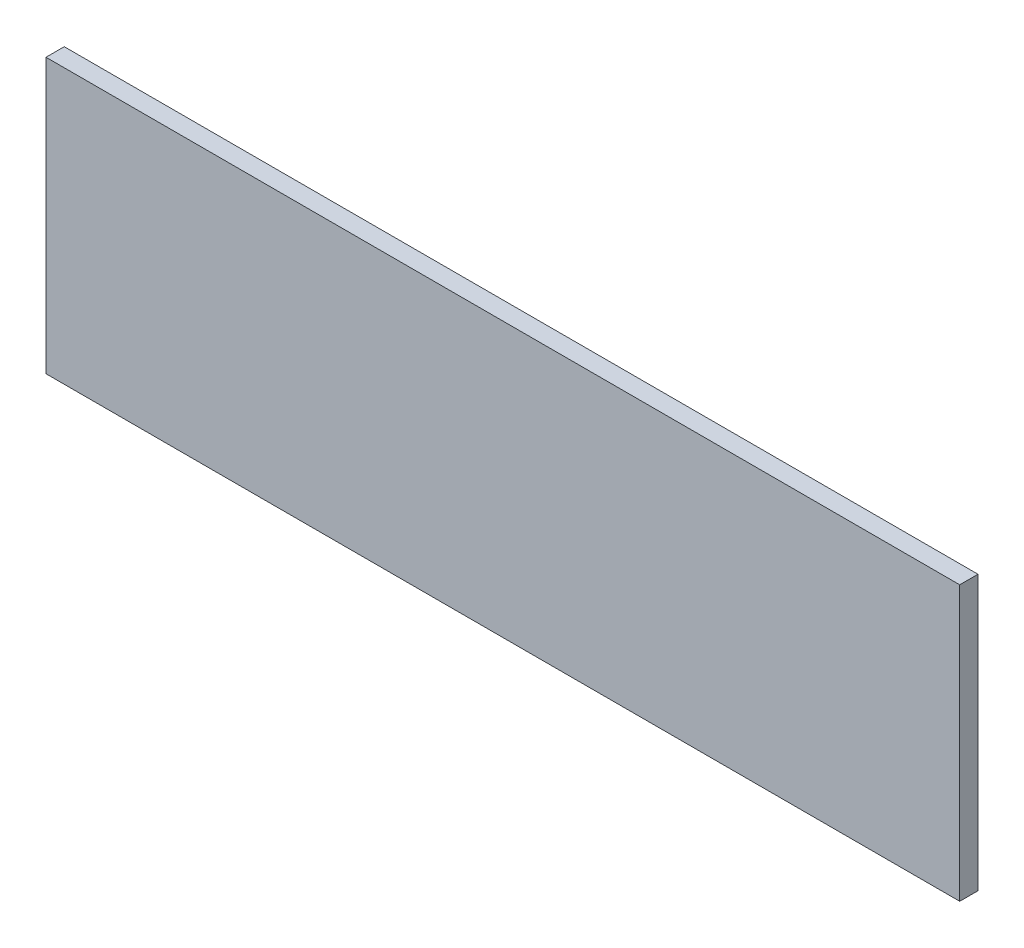
SolidWorks part; units mm, degrees
ref_plane "Front Plane" through (0, 0, 0) normal (0, 0, 1) x (1, 0, 0)
ref_plane "Top Plane" through (0, 0, 0) normal (0, 1, 0) x (1, 0, 0)
ref_plane "Right Plane" through (0, 0, 0) normal (1, 0, 0) x (0, 0, -1)
sketch "Sketch1" plane through (0, 0, 0) normal (0, 0, 1) x (1, 0, 0)
  line L1 (1.3535, 24.2721) -> (-125.6465, 24.2721)
  line L2 (1.3535, 24.2721) -> (1.3535, 62.3721)
  line L3 (1.3535, 62.3721) -> (-125.6465, 62.3721)
  line L4 (-125.6465, 24.2721) -> (-125.6465, 62.3721)
  dimension "D1" = 127
  dimension "D2" = 38.1
extrude "Boss-Extrude1" add sketch "Sketch1" along normal blind 2.54
